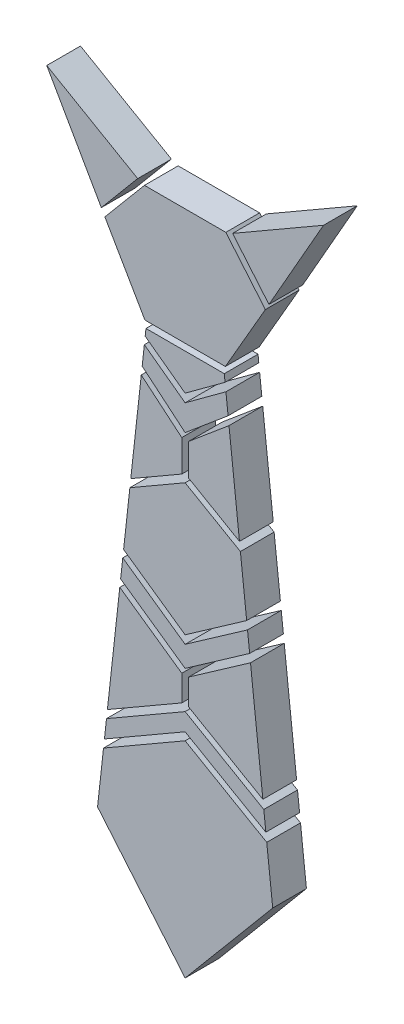
SolidWorks part; units mm, degrees
ref_plane "Front Plane" through (0, 0, 0) normal (0, 0, 1) x (1, 0, 0)
ref_plane "Top Plane" through (0, 0, 0) normal (0, 1, 0) x (1, 0, 0)
ref_plane "Right Plane" through (0, 0, 0) normal (1, 0, 0) x (0, 0, -1)
sketch "Mastersketch" plane through (0, 0, 0) normal (0, 0, 1) x (1, 0, 0)
  line L0 (0, 127) -> (0, -127) construction
  line L1 (-31.75, 108.1303) -> (31.75, 108.1303) construction
  line L2 (-34.29, -86.1348) -> (34.29, -86.1348) construction
  line L6 (-31.75, 108.1303) -> (-15.875, 80.634)
  line L7 (-15.875, 80.634) -> (15.875, 80.634)
  line L8 (15.875, 80.634) -> (31.75, 108.1303)
  line L9 (0, -127) -> (34.29, -86.1348)
  line L16 (-34.29, -86.1348) -> (0, -127)
  line L17 (-15.875, 80.634) -> (-34.29, -86.1348) construction
  line L18 (15.875, 80.634) -> (34.29, -86.1348) construction
  line L19 (-15.9164, 127) -> (15.9164, 127)
  line L20 (31.75, 108.1303) -> (15.875, 135.6266)
  line L21 (-15.875, 135.6266) -> (-31.75, 108.1303)
  line L22 (15.875, 135.6266) -> (-15.875, 135.6266)
  line L23 (15.9164, 127) -> (31.75, 108.1303)
  line L24 (-15.9164, 127) -> (-31.75, 108.1303)
  line L25 (0, 64.0649) -> (-16.3762, 76.095)
  line L26 (0, 64.0649) -> (16.3762, 76.095)
  line L27 (-17.5118, 65.8111) -> (0, 51.117)
  line L34 (0, 51.117) -> (17.5118, 65.8111)
  line L35 (0, 51.117) -> (0, 37.8919)
  line L36 (0, 37.8919) -> (21.997, 25.1919)
  line L37 (21.997, 25.1919) -> (17.5118, 65.8111)
  line L38 (21.997, 25.1919) -> (24.5061, 2.47)
  line L39 (24.5061, 2.47) -> (0, -14.6893)
  line L40 (0, -14.6893) -> (-24.5061, 2.47)
  line L41 (-24.5061, 2.47) -> (-21.997, 25.1919)
  line L42 (-21.997, 25.1919) -> (0, 37.8919)
  line L43 (-17.5118, 65.8111) -> (-21.997, 25.1919)
  line L44 (-16.3762, 76.095) -> (-17.5118, 65.8111)
  line L45 (16.3762, 76.095) -> (17.5118, 65.8111)
  line L46 (15.875, 80.634) -> (16.3762, 76.095)
  line L47 (-15.875, 80.634) -> (-16.3762, 76.095)
  line L48 (-25.6279, -7.69) -> (0, -25.6349)
  line L49 (0, -25.6349) -> (25.6279, -7.69)
  line L50 (25.6279, -7.69) -> (30.7959, -54.4914)
  line L51 (30.7959, -54.4914) -> (0, -36.7114)
  line L52 (0, -36.7114) -> (0, -25.6349)
  line L53 (-30.7959, -54.4914) -> (0, -36.7114)
  line L54 (-30.7959, -54.4914) -> (-25.6279, -7.69)
  line L55 (25.6279, -7.69) -> (24.5061, 2.47)
  line L56 (-25.6279, -7.69) -> (-24.5061, 2.47)
  line L57 (-30.7959, -54.4914) -> (-31.9178, -64.6514)
  line L58 (31.9178, -64.6514) -> (34.29, -86.1348)
  line L60 (-31.9178, -64.6514) -> (-34.29, -86.1348)
  line L61 (15.9164, 127) -> (55.5111, 149.86)
  line L62 (55.5111, 149.86) -> (31.75, 108.1303)
  line L63 (-15.9164, 127) -> (-55.5111, 149.86)
  line L64 (-55.5111, 149.86) -> (-31.75, 108.1303)
  line L65 (-31.9178, -64.6514) -> (0, -46.2237)
  line L66 (0, -46.2237) -> (31.9178, -64.6514)
  line L67 (-30.7959, -54.4914) -> (-31.9178, -64.6514)
  line L68 (30.7959, -54.4914) -> (31.9178, -64.6514)
  point P15 (0, -86.1348)
  dimension "D1" = 254
  dimension "D2" = 63.5
  dimension "D3" = 68.58
  dimension "D4" = 130
  dimension "D5" = 130
  dimension "D6" = 31.8329
  dimension "D7" = 20.32
  dimension "D8" = 120
  dimension "D9" = 50
  dimension "D10" = 150
  dimension "D11" = 45.72
  dimension "D12" = 31.75
  dimension "D13" = 22.86
  dimension "D14" = 25.4
  dimension "D15" = 25.4
  dimension "D16" = 22.86
  dimension "D17" = 100
  dimension "D18" = 120
  dimension "D19" = 110
  dimension "D20" = 22.86
  dimension "D21" = 22.86
  dimension "D22" = 10.16
  dimension "D23" = 10.16
  dimension "D24" = 120
  dimension "D25" = 35.56
  dimension "D26" = 10.16
sketch "Offset_Pieces" plane through (0, 0, 0) normal (0, 0, 1) x (1, 0, 0)
  line L8 (-52.09, 146.4183) -> (-31.5496, 110.3449)
  line L9 (-17.8622, 126.6569) -> (-52.09, 146.4183)
  line L10 (-31.5496, 110.3449) -> (-17.8622, 126.6569)
  line L11 (-52.09, 146.4183) -> (-31.5496, 110.3449)
  line L12 (-17.8622, 126.6569) -> (-52.09, 146.4183)
  line L13 (-31.5496, 110.3449) -> (-17.8622, 126.6569)
  line L28 (15.0334, 76.6844) -> (14.7375, 79.364)
  line L29 (14.7375, 79.364) -> (-14.7375, 79.364)
  line L30 (-14.7375, 79.364) -> (-15.0334, 76.6844)
  line L31 (-15.0334, 76.6844) -> (0, 65.6408)
  line L32 (0, 65.6408) -> (15.0334, 76.6844)
  line L33 (15.0334, 76.6844) -> (14.7375, 79.364)
  line L34 (14.7375, 79.364) -> (-14.7375, 79.364)
  line L35 (-14.7375, 79.364) -> (-15.0334, 76.6844)
  line L36 (-15.0334, 76.6844) -> (0, 65.6408)
  line L37 (0, 65.6408) -> (15.0334, 76.6844)
  line L52 (-15.1418, 81.904) -> (15.1418, 81.904)
  line L53 (-30.2055, 107.9952) -> (-15.1418, 81.904)
  line L54 (-15.3242, 125.73) -> (-30.2055, 107.9952)
  line L55 (15.1418, 81.904) -> (30.2055, 107.9952)
  line L56 (30.2055, 107.9952) -> (15.3242, 125.73)
  line L57 (15.3242, 125.73) -> (-15.3242, 125.73)
  line L58 (-15.1418, 81.904) -> (15.1418, 81.904)
  line L59 (-30.2055, 107.9952) -> (-15.1418, 81.904)
  line L60 (-15.3242, 125.73) -> (-30.2055, 107.9952)
  line L61 (15.1418, 81.904) -> (30.2055, 107.9952)
  line L62 (30.2055, 107.9952) -> (15.3242, 125.73)
  line L63 (15.3242, 125.73) -> (-15.3242, 125.73)
  line L66 (31.5496, 110.3449) -> (52.09, 146.4183)
  line L67 (52.09, 146.4183) -> (17.8622, 126.6569)
  line L68 (17.8622, 126.6569) -> (31.5496, 110.3449)
  line L69 (31.5496, 110.3449) -> (52.09, 146.4183)
  line L70 (52.09, 146.4183) -> (17.8622, 126.6569)
  line L71 (17.8622, 126.6569) -> (31.5496, 110.3449)
  line L77 (15.3553, 73.7692) -> (0, 62.4891)
  line L78 (16.1749, 66.3472) -> (15.3553, 73.7692)
  line L79 (0, 52.7749) -> (16.1749, 66.3472)
  line L80 (-16.1749, 66.3472) -> (0, 52.7749)
  line L81 (-15.3553, 73.7692) -> (-16.1749, 66.3472)
  line L82 (0, 62.4891) -> (-15.3553, 73.7692)
  line L83 (15.3553, 73.7692) -> (0, 62.4891)
  line L84 (16.1749, 66.3472) -> (15.3553, 73.7692)
  line L85 (0, 52.7749) -> (16.1749, 66.3472)
  line L86 (-16.1749, 66.3472) -> (0, 52.7749)
  line L87 (-15.3553, 73.7692) -> (-16.1749, 66.3472)
  line L88 (0, 62.4891) -> (-15.3553, 73.7692)
  line L96 (20.4594, 27.5462) -> (16.5099, 63.3126)
  line L97 (1.27, 38.6251) -> (20.4594, 27.5462)
  line L98 (1.27, 50.5248) -> (1.27, 38.6251)
  line L99 (16.5099, 63.3126) -> (1.27, 50.5248)
  line L100 (20.4594, 27.5462) -> (16.5099, 63.3126)
  line L101 (1.27, 38.6251) -> (20.4594, 27.5462)
  line L102 (1.27, 50.5248) -> (1.27, 38.6251)
  line L103 (16.5099, 63.3126) -> (1.27, 50.5248)
  line L113 (-1.27, 50.5248) -> (-16.5099, 63.3126)
  line L114 (-16.5099, 63.3126) -> (-20.4594, 27.5462)
  line L115 (-20.4594, 27.5462) -> (-1.27, 38.6251)
  line L116 (-1.27, 38.6251) -> (-1.27, 50.5248)
  line L117 (-1.27, 50.5248) -> (-16.5099, 63.3126)
  line L118 (-16.5099, 63.3126) -> (-20.4594, 27.5462)
  line L119 (-20.4594, 27.5462) -> (-1.27, 38.6251)
  line L120 (-1.27, 38.6251) -> (-1.27, 50.5248)
  line L143 (0, -13.1389) -> (23.1611, 3.0787)
  line L144 (23.1611, 3.0787) -> (20.8053, 24.4135)
  line L145 (20.8053, 24.4135) -> (0, 36.4254)
  line L146 (-23.1611, 3.0787) -> (0, -13.1389)
  line L147 (-20.8053, 24.4135) -> (-23.1611, 3.0787)
  line L148 (0, 36.4254) -> (-20.8053, 24.4135)
  line L149 (0, -13.1389) -> (23.1611, 3.0787)
  line L150 (23.1611, 3.0787) -> (20.8053, 24.4135)
  line L151 (20.8053, 24.4135) -> (0, 36.4254)
  line L152 (-23.1611, 3.0787) -> (0, -13.1389)
  line L153 (-20.8053, 24.4135) -> (-23.1611, 3.0787)
  line L154 (0, 36.4254) -> (-20.8053, 24.4135)
  line L175 (24.283, -7.0813) -> (23.4789, 0.2004)
  line L176 (23.4789, 0.2004) -> (0, -16.2397)
  line L177 (0, -24.0845) -> (24.283, -7.0813)
  line L178 (-24.283, -7.0813) -> (0, -24.0845)
  line L179 (-23.4789, 0.2004) -> (-24.283, -7.0813)
  line L180 (0, -16.2397) -> (-23.4789, 0.2004)
  line L181 (24.283, -7.0813) -> (23.4789, 0.2004)
  line L182 (23.4789, 0.2004) -> (0, -16.2397)
  line L183 (0, -24.0845) -> (24.283, -7.0813)
  line L184 (-24.283, -7.0813) -> (0, -24.0845)
  line L185 (-23.4789, 0.2004) -> (-24.283, -7.0813)
  line L186 (0, -16.2397) -> (-23.4789, 0.2004)
  line L194 (-24.6008, -9.9596) -> (-29.2582, -52.1371)
  line L195 (-29.2582, -52.1371) -> (-1.27, -35.9782)
  line L196 (-1.27, -26.296) -> (-24.6008, -9.9596)
  line L197 (-1.27, -35.9782) -> (-1.27, -26.296)
  line L198 (-24.6008, -9.9596) -> (-29.2582, -52.1371)
  line L199 (-29.2582, -52.1371) -> (-1.27, -35.9782)
  line L200 (-1.27, -26.296) -> (-24.6008, -9.9596)
  line L201 (-1.27, -35.9782) -> (-1.27, -26.296)
  line L211 (1.27, -26.296) -> (1.27, -35.9782)
  line L212 (24.6008, -9.9596) -> (1.27, -26.296)
  line L213 (1.27, -35.9782) -> (29.2582, -52.1371)
  line L214 (29.2582, -52.1371) -> (24.6008, -9.9596)
  line L215 (1.27, -26.296) -> (1.27, -35.9782)
  line L216 (24.6008, -9.9596) -> (1.27, -26.296)
  line L217 (1.27, -35.9782) -> (29.2582, -52.1371)
  line L218 (29.2582, -52.1371) -> (24.6008, -9.9596)
  line L241 (30.3801, -62.2971) -> (29.6041, -55.2698)
  line L242 (0, -44.7572) -> (30.3801, -62.2971)
  line L243 (29.6041, -55.2698) -> (0, -38.1779)
  line L244 (0, -38.1779) -> (-29.6041, -55.2698)
  line L245 (-30.3801, -62.2971) -> (0, -44.7572)
  line L246 (-29.6041, -55.2698) -> (-30.3801, -62.2971)
  line L247 (30.3801, -62.2971) -> (29.6041, -55.2698)
  line L248 (0, -44.7572) -> (30.3801, -62.2971)
  line L249 (29.6041, -55.2698) -> (0, -38.1779)
  line L250 (0, -38.1779) -> (-29.6041, -55.2698)
  line L251 (-30.3801, -62.2971) -> (0, -44.7572)
  line L252 (-29.6041, -55.2698) -> (-30.3801, -62.2971)
  line L273 (-30.726, -65.4298) -> (-32.9681, -85.7344)
  line L274 (-32.9681, -85.7344) -> (0, -125.0242)
  line L275 (0, -125.0242) -> (32.9681, -85.7344)
  line L276 (32.9681, -85.7344) -> (30.726, -65.4298)
  line L277 (30.726, -65.4298) -> (0, -47.6901)
  line L278 (0, -47.6901) -> (-30.726, -65.4298)
  line L279 (-30.726, -65.4298) -> (-32.9681, -85.7344)
  line L280 (-32.9681, -85.7344) -> (0, -125.0242)
  line L281 (0, -125.0242) -> (32.9681, -85.7344)
  line L282 (32.9681, -85.7344) -> (30.726, -65.4298)
  line L283 (30.726, -65.4298) -> (0, -47.6901)
  line L284 (0, -47.6901) -> (-30.726, -65.4298)
  dimension "D1" = 1.27
  dimension "D2" = 1.27
  dimension "D3" = 1.27
  dimension "D4" = 1.27
  dimension "D5" = 1.27
  dimension "D6" = 1.27
  dimension "D7" = 1.27
  dimension "D8" = 1.27
  dimension "D9" = 1.27
  dimension "D10" = 1.27
  dimension "D11" = 1.27
  dimension "D12" = 1.27
  dimension "D13" = 1.27
extrude "Boss-Extrude1" add sketch "Offset_Pieces" along normal blind 12.7
